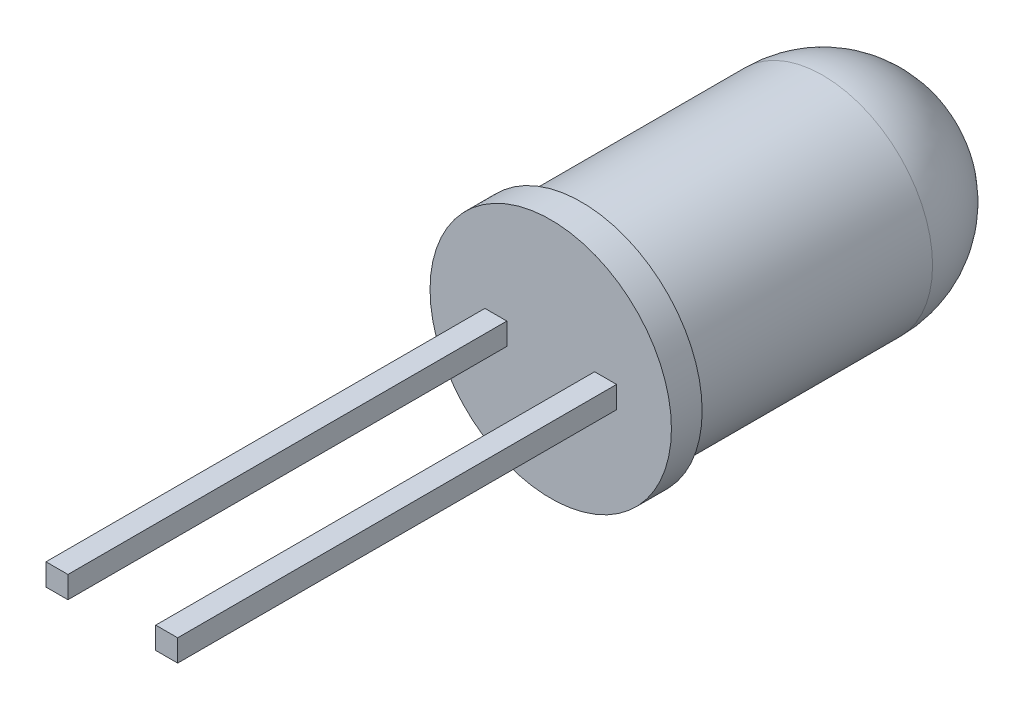
SolidWorks part; units mm, degrees
ref_plane "Plan de face" through (0, 0, 0) normal (0, 0, 1) x (1, 0, 0)
ref_plane "Plan de dessus" through (0, 0, 0) normal (0, 1, 0) x (1, 0, 0)
ref_plane "Plan de droite" through (0, 0, 0) normal (1, 0, 0) x (0, 0, -1)
sketch "Esquisse1" plane through (0, 0, 0) normal (0, 0, 1) x (1, 0, 0)
  circle A0 centre (0, 0) radius 2.5
  dimension "D1" = 5
extrude "Boss.-Extru.1" add sketch "Esquisse1" along normal blind 8
sketch "Esquisse2" plane through (0, 0, 8) normal (0, 0, 1) x (1, 0, 0)
  circle A0 centre (0, 0) radius 2.75
  dimension "D1" = 5.5
extrude "Boss.-Extru.2" add sketch "Esquisse2" along normal blind 0.7
sketch "Esquisse3" plane through (0, 0, 8.7) normal (0, 0, 1) x (1, 0, 0)
  line L0 (1, 0) -> (-1, 0) construction
  line L1 (-1.5, 0.25) -> (-1, 0.25)
  line L2 (-1.5, 0.25) -> (-1.5, -0.25)
  line L3 (-1.5, -0.25) -> (-1, -0.25)
  line L4 (-1, 0.25) -> (-1, -0.25)
  line L5 (1, 0.25) -> (1.5, 0.25)
  line L6 (1, 0.25) -> (1, -0.25)
  line L7 (1, -0.25) -> (1.5, -0.25)
  line L8 (1.5, 0.25) -> (1.5, -0.25)
  circle A1 centre (0, 0) radius 2.75
  circle A2 centre (0, 0) radius 2.75 construction
  point P8 (1, 0)
  point P9 (0, 0)
  point P12 (0, 0)
  point P16 (-1.25, -0.25)
  point P17 (1.25, -0.25)
  dimension "D1" = 0.5
  dimension "D4" = 2.5
  dimension "D2" = 0
extrude "Boss.-Extru.3" add sketch "Esquisse3" along normal blind 10
fillet "Congé1" radius 2.5 1 edges at (2.5, 0, 0)
